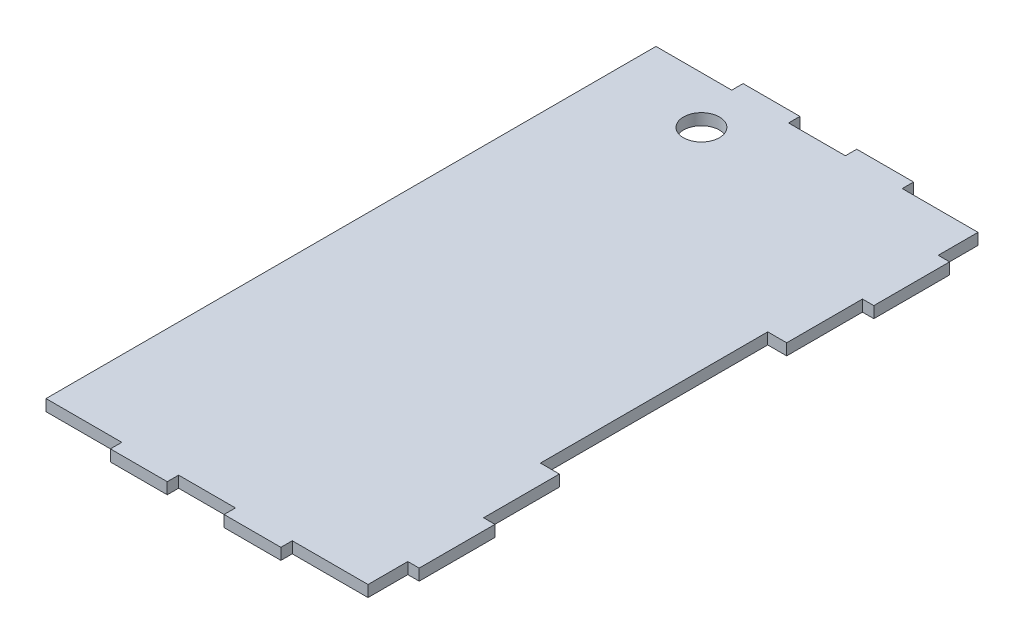
SolidWorks part; units mm, degrees
ref_plane "Alzado" through (0, 0, 0) normal (0, 0, 1) x (1, 0, 0)
ref_plane "Planta" through (0, 0, 0) normal (0, 1, 0) x (1, 0, 0)
ref_plane "Vista lateral" through (0, 0, 0) normal (1, 0, 0) x (0, 0, -1)
sketch "Croquis1" plane through (0, 0, 0) normal (0, 1, 0) x (1, 0, 0)
  line L0 (25.5, -0.5) -> (40.5, -0.5)
  line L1 (93.5, 13) -> (93.5, 33)
  line L2 (90.5, 163.5) -> (70.5, 163.5)
  line L3 (90.5, 113) -> (85.5, 113)
  line L4 (5.5, 163.5) -> (5.5, 2.5)
  line L5 (5.5, 73) -> (5.5, 93)
  line L6 (55.5, 166.5) -> (70.5, 166.5)
  line L7 (55.5, 163.5) -> (55.5, 166.5)
  line L8 (70.5, 166.5) -> (70.5, 163.5)
  line L9 (5.5, 113) -> (5.5, 133)
  line L10 (25.5, 166.5) -> (25.5, 163.5)
  line L11 (40.5, 166.5) -> (25.5, 166.5)
  line L12 (40.5, 163.5) -> (40.5, 166.5)
  line L13 (25.5, 166.5) -> (40.5, 166.5)
  line L14 (25.5, 163.5) -> (5.5, 163.5)
  line L15 (5.5, 53) -> (5.5, 33)
  line L16 (55.5, 163.5) -> (40.5, 163.5)
  line L17 (40.5, 2.5) -> (55.5, 2.5)
  line L18 (5.5, 153) -> (5.5, 163.5)
  line L19 (5.5, 13) -> (5.5, 2.5)
  line L20 (70.5, 2.5) -> (90.5, 2.5)
  line L21 (55.5, 2.5) -> (40.5, 2.5)
  line L22 (40.5, 2.5) -> (40.5, -0.5)
  line L23 (40.5, -0.5) -> (25.5, -0.5)
  line L24 (25.5, -0.5) -> (25.5, 2.5)
  line L25 (25.5, 2.5) -> (5.5, 2.5)
  line L26 (70.5, 2.5) -> (90.5, 2.5)
  line L27 (70.5, -0.5) -> (70.5, 2.5)
  line L28 (55.5, 2.5) -> (55.5, -0.5)
  line L29 (90.5, 13) -> (90.5, 2.5)
  line L30 (90.5, 153) -> (90.5, 163.5)
  line L31 (25.5, 163.5) -> (25.5, 151) construction
  line L32 (93.5, 151) -> (30, 151) construction
  line L33 (90.5, 53) -> (90.5, 33)
  line L34 (90.5, 33) -> (93.5, 33)
  line L35 (93.5, 13) -> (90.5, 13)
  line L36 (93.5, 153) -> (90.5, 153)
  line L37 (90.5, 133) -> (93.5, 133)
  line L38 (90.5, 113) -> (90.5, 133)
  line L42 (93.5, 133) -> (93.5, 153)
  line L43 (55.5, -0.5) -> (70.5, -0.5)
  line L46 (85.5, 113) -> (85.5, 53)
  line L47 (85.5, 53) -> (90.5, 53)
  line L48 (5.5, 2.5) -> (25.5, 2.5)
  line L49 (5.5, 163.5) -> (5.5, 13)
  circle A0 centre (30, 151) radius 4.75
  dimension "D4" = 85
  dimension "D15" = 9.5
  dimension "D2" = 10.5
  dimension "D3" = 10.5
  dimension "D5" = 5
  dimension "D6" = 20
  dimension "D7" = 12.5
  dimension "D8" = 10.5
  dimension "D9" = 10.5
  dimension "D10" = 15
  dimension "D11" = 20
  dimension "D12" = 20
  dimension "D13" = 3
  dimension "D14" = 63.5
extrude "Saliente-Extruir1" add sketch "Croquis1" along normal blind 3
